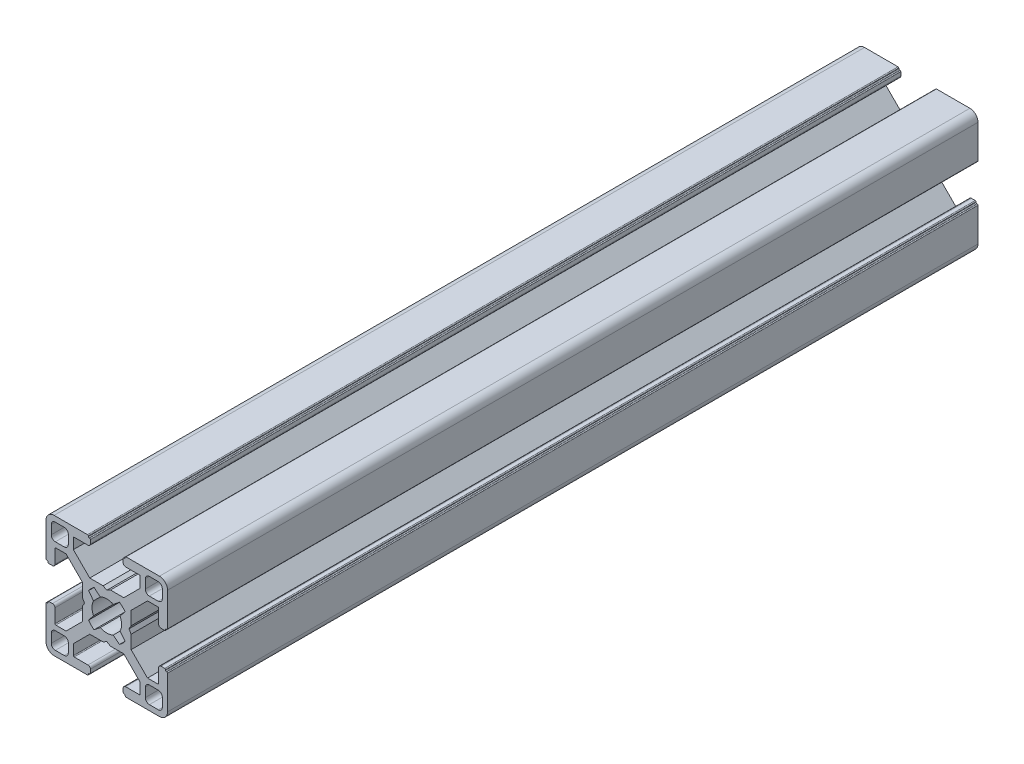
SolidWorks part; units mm, degrees
ref_plane "Front" through (0, 0, 0) normal (0, 0, 1) x (1, 0, 0)
ref_plane "Top" through (0, 0, 0) normal (0, 1, 0) x (1, 0, 0)
ref_plane "Right" through (0, 0, 0) normal (1, 0, 0) x (0, 0, -1)
sketch "Sketch1" plane through (0, 0, 0) normal (0, 0, 1) x (1, 0, 0)
  line L0 (13.7, 12.7) -> (13.7, 10.5)
  line L1 (10.5, 9.5) -> (12.7, 9.5)
  line L2 (9.5, 12.7) -> (9.5, 10.5)
  line L3 (10.5, 13.7) -> (12.7, 13.7)
  line L4 (3.1359, 4.5184) -> (1.6001, 3.2806)
  line L5 (3.2806, 1.6001) -> (4.5053, 3.1547)
  line L6 (6.0045, 0.9) -> (5.4849, 0)
  line L7 (6.0045, 4.2045) -> (6.0045, 0.9)
  line L8 (0, -5.4849) -> (0.9, -6)
  line L9 (0.9, -6) -> (4.2045, -6)
  line L10 (4.2045, -6) -> (8.25, -10.05)
  line L11 (8.25, -10.05) -> (8.25, -12.6)
  line L12 (4.65, -12.8) -> (8.05, -12.8)
  line L13 (4.05, -14.3) -> (4.05, -13.4)
  line L14 (4.25, -14.5) -> (4.35, -14.5)
  line L15 (4.55, -14.8) -> (4.55, -14.7)
  line L16 (4.75, -15) -> (13, -15)
  line L17 (15, -13) -> (15, -4.75)
  line L18 (14.7, -4.55) -> (14.8, -4.55)
  line L19 (14.5, -4.35) -> (14.5, -4.25)
  line L20 (13.4, -4.05) -> (14.3, -4.05)
  line L21 (12.8, -8.05) -> (12.8, -4.65)
  line L22 (12.6, -8.25) -> (10.05, -8.25)
  line L23 (10.05, -8.25) -> (6.0045, -4.2045)
  line L24 (6.0045, -4.2045) -> (6.0045, -0.9)
  line L25 (6.0045, -0.9) -> (5.4849, 0)
  line L26 (10.05, 8.25) -> (6.0045, 4.2045)
  line L27 (12.6, 8.25) -> (10.05, 8.25)
  line L28 (12.8, 8.05) -> (12.8, 4.65)
  line L29 (13.4, 4.05) -> (14.3, 4.05)
  line L30 (14.5, 4.35) -> (14.5, 4.25)
  line L31 (14.7, 4.55) -> (14.8, 4.55)
  line L32 (15, 13) -> (15, 4.75)
  line L33 (4.75, 15) -> (13, 15)
  line L34 (4.55, 14.8) -> (4.55, 14.7)
  line L35 (4.25, 14.5) -> (4.35, 14.5)
  line L36 (4.05, 14.3) -> (4.05, 13.4)
  line L37 (4.65, 12.8) -> (8.05, 12.8)
  line L38 (8.25, 10.05) -> (8.25, 12.6)
  line L39 (4.2045, 6) -> (8.25, 10.05)
  line L40 (0.9, 6) -> (4.2045, 6)
  line L41 (0, 5.4849) -> (0.9, 6)
  line L42 (-13.7, -12.7) -> (-13.7, -10.5)
  line L43 (-10.5, -9.5) -> (-12.7, -9.5)
  line L44 (-9.5, -12.7) -> (-9.5, -10.5)
  line L45 (-10.5, -13.7) -> (-12.7, -13.7)
  line L46 (-3.1359, -4.5184) -> (-1.6001, -3.2806)
  line L47 (-3.2806, -1.6001) -> (-4.5053, -3.1547)
  line L48 (0, 5.4849) -> (-0.9, 6)
  line L49 (-0.9, 6) -> (-4.2045, 6)
  line L50 (-4.2045, 6) -> (-8.25, 10.05)
  line L51 (-8.25, 10.05) -> (-8.25, 12.6)
  line L52 (-4.65, 12.8) -> (-8.05, 12.8)
  line L53 (-4.05, 14.3) -> (-4.05, 13.4)
  line L54 (-4.25, 14.5) -> (-4.35, 14.5)
  line L55 (-4.55, 14.8) -> (-4.55, 14.7)
  line L56 (-4.75, 15) -> (-13, 15)
  line L57 (-15, 13) -> (-15, 4.75)
  line L58 (-14.7, 4.55) -> (-14.8, 4.55)
  line L59 (-14.5, 4.35) -> (-14.5, 4.25)
  line L60 (-13.4, 4.05) -> (-14.3, 4.05)
  line L61 (-12.8, 8.05) -> (-12.8, 4.65)
  line L62 (-12.6, 8.25) -> (-10.05, 8.25)
  line L63 (-10.05, 8.25) -> (-6.0045, 4.2045)
  line L64 (-6.0045, -0.9) -> (-5.4849, 0)
  line L65 (-6.0045, -4.2045) -> (-6.0045, -0.9)
  line L66 (-10.05, -8.25) -> (-6.0045, -4.2045)
  line L67 (-12.6, -8.25) -> (-10.05, -8.25)
  line L68 (-12.8, -8.05) -> (-12.8, -4.65)
  line L69 (-13.4, -4.05) -> (-14.3, -4.05)
  line L70 (-14.5, -4.35) -> (-14.5, -4.25)
  line L71 (-14.7, -4.55) -> (-14.8, -4.55)
  line L72 (-15, -13) -> (-15, -4.75)
  line L73 (-4.75, -15) -> (-13, -15)
  line L74 (-4.55, -14.8) -> (-4.55, -14.7)
  line L75 (-4.25, -14.5) -> (-4.35, -14.5)
  line L76 (-4.05, -14.3) -> (-4.05, -13.4)
  line L77 (3.2806, -1.6001) -> (4.5053, -3.1547)
  line L78 (3.1359, -4.5184) -> (1.6001, -3.2806)
  line L79 (-4.65, -12.8) -> (-8.05, -12.8)
  line L80 (-8.25, -10.05) -> (-8.25, -12.6)
  line L81 (-4.2045, -6) -> (-8.25, -10.05)
  line L82 (-0.9, -6) -> (-4.2045, -6)
  line L83 (0, -5.4849) -> (-0.9, -6)
  line L84 (10.5, -13.7) -> (12.7, -13.7)
  line L85 (9.5, -12.7) -> (9.5, -10.5)
  line L86 (10.5, -9.5) -> (12.7, -9.5)
  line L87 (13.7, -12.7) -> (13.7, -10.5)
  line L88 (-6.0045, 4.2045) -> (-6.0045, 0.9)
  line L89 (-6.0045, 0.9) -> (-5.4849, 0)
  line L90 (-3.2806, 1.6001) -> (-4.5053, 3.1547)
  line L91 (-3.1359, 4.5184) -> (-1.6001, 3.2806)
  line L92 (-10.5, 13.7) -> (-12.7, 13.7)
  line L93 (-9.5, 12.7) -> (-9.5, 10.5)
  line L94 (-10.5, 9.5) -> (-12.7, 9.5)
  line L95 (-13.7, 12.7) -> (-13.7, 10.5)
  line L96 (-23.4857, 0) -> (20.9308, 0) construction
  line L97 (0, 17.9563) -> (0, -17.361) construction
  arc A0 (13.7, 12.7) -> (12.7, 13.7) centre (12.7, 12.7) ccw
  arc A1 (12.7, 9.5) -> (13.7, 10.5) centre (12.7, 10.5) ccw
  arc A2 (9.5, 10.5) -> (10.5, 9.5) centre (10.5, 10.5) ccw
  arc A3 (10.5, 13.7) -> (9.5, 12.7) centre (10.5, 12.7) ccw
  arc A4 (1.6001, 3.2806) -> (-1.6001, 3.2806) centre (0, 0) ccw
  arc A5 (8.25, -12.6) -> (8.05, -12.8) centre (8.05, -12.6) cw
  arc A6 (4.65, -12.8) -> (4.05, -13.4) centre (4.65, -13.4) ccw
  arc A7 (4.05, -14.3) -> (4.25, -14.5) centre (4.25, -14.3) ccw
  arc A8 (4.35, -14.5) -> (4.55, -14.7) centre (4.35, -14.7) cw
  arc A9 (4.55, -14.8) -> (4.75, -15) centre (4.75, -14.8) ccw
  arc A10 (13, -15) -> (15, -13) centre (13, -13) ccw
  arc A11 (15, -4.75) -> (14.8, -4.55) centre (14.8, -4.75) ccw
  arc A12 (14.7, -4.55) -> (14.5, -4.35) centre (14.7, -4.35) cw
  arc A13 (14.5, -4.25) -> (14.3, -4.05) centre (14.3, -4.25) ccw
  arc A14 (13.4, -4.05) -> (12.8, -4.65) centre (13.4, -4.65) ccw
  arc A15 (12.8, -8.05) -> (12.6, -8.25) centre (12.6, -8.05) cw
  arc A16 (4.5053, 3.1547) -> (3.1359, 4.5184) centre (0, 0) ccw
  arc A17 (12.8, 8.05) -> (12.6, 8.25) centre (12.6, 8.05) ccw
  arc A18 (13.4, 4.05) -> (12.8, 4.65) centre (13.4, 4.65) cw
  arc A19 (14.5, 4.25) -> (14.3, 4.05) centre (14.3, 4.25) cw
  arc A20 (14.7, 4.55) -> (14.5, 4.35) centre (14.7, 4.35) ccw
  arc A21 (15, 4.75) -> (14.8, 4.55) centre (14.8, 4.75) cw
  arc A22 (13, 15) -> (15, 13) centre (13, 13) cw
  arc A23 (4.55, 14.8) -> (4.75, 15) centre (4.75, 14.8) cw
  arc A24 (4.35, 14.5) -> (4.55, 14.7) centre (4.35, 14.7) ccw
  arc A25 (4.05, 14.3) -> (4.25, 14.5) centre (4.25, 14.3) cw
  arc A26 (4.65, 12.8) -> (4.05, 13.4) centre (4.65, 13.4) cw
  arc A27 (8.25, 12.6) -> (8.05, 12.8) centre (8.05, 12.6) ccw
  arc A28 (-13.7, -12.7) -> (-12.7, -13.7) centre (-12.7, -12.7) ccw
  arc A29 (-12.7, -9.5) -> (-13.7, -10.5) centre (-12.7, -10.5) ccw
  arc A30 (-9.5, -10.5) -> (-10.5, -9.5) centre (-10.5, -10.5) ccw
  arc A31 (-10.5, -13.7) -> (-9.5, -12.7) centre (-10.5, -12.7) ccw
  arc A32 (-4.5053, -3.1547) -> (-3.1359, -4.5184) centre (0, 0) ccw
  arc A33 (-3.2806, 1.6001) -> (-3.2806, -1.6001) centre (0, 0) ccw
  arc A34 (-8.25, 12.6) -> (-8.05, 12.8) centre (-8.05, 12.6) cw
  arc A35 (-4.65, 12.8) -> (-4.05, 13.4) centre (-4.65, 13.4) ccw
  arc A36 (-4.05, 14.3) -> (-4.25, 14.5) centre (-4.25, 14.3) ccw
  arc A37 (-4.35, 14.5) -> (-4.55, 14.7) centre (-4.35, 14.7) cw
  arc A38 (-4.55, 14.8) -> (-4.75, 15) centre (-4.75, 14.8) ccw
  arc A39 (-13, 15) -> (-15, 13) centre (-13, 13) ccw
  arc A40 (-15, 4.75) -> (-14.8, 4.55) centre (-14.8, 4.75) ccw
  arc A41 (-14.7, 4.55) -> (-14.5, 4.35) centre (-14.7, 4.35) cw
  arc A42 (-14.5, 4.25) -> (-14.3, 4.05) centre (-14.3, 4.25) ccw
  arc A43 (-13.4, 4.05) -> (-12.8, 4.65) centre (-13.4, 4.65) ccw
  arc A44 (-12.8, 8.05) -> (-12.6, 8.25) centre (-12.6, 8.05) cw
  arc A45 (-4.5053, 3.1547) -> (-3.1359, 4.5184) centre (0, 0) cw
  arc A46 (-12.8, -8.05) -> (-12.6, -8.25) centre (-12.6, -8.05) ccw
  arc A47 (-13.4, -4.05) -> (-12.8, -4.65) centre (-13.4, -4.65) cw
  arc A48 (-14.5, -4.25) -> (-14.3, -4.05) centre (-14.3, -4.25) cw
  arc A49 (3.2806, 1.6001) -> (3.2806, -1.6001) centre (0, 0) cw
  arc A50 (4.5053, -3.1547) -> (3.1359, -4.5184) centre (0, 0) cw
  arc A51 (1.6001, -3.2806) -> (-1.6001, -3.2806) centre (0, 0) cw
  arc A52 (-14.7, -4.55) -> (-14.5, -4.35) centre (-14.7, -4.35) ccw
  arc A53 (-15, -4.75) -> (-14.8, -4.55) centre (-14.8, -4.75) cw
  arc A54 (-13, -15) -> (-15, -13) centre (-13, -13) cw
  arc A55 (-4.55, -14.8) -> (-4.75, -15) centre (-4.75, -14.8) cw
  arc A56 (10.5, -13.7) -> (9.5, -12.7) centre (10.5, -12.7) cw
  arc A57 (9.5, -10.5) -> (10.5, -9.5) centre (10.5, -10.5) cw
  arc A58 (12.7, -9.5) -> (13.7, -10.5) centre (12.7, -10.5) cw
  arc A59 (13.7, -12.7) -> (12.7, -13.7) centre (12.7, -12.7) cw
  arc A60 (-4.35, -14.5) -> (-4.55, -14.7) centre (-4.35, -14.7) ccw
  arc A61 (-4.05, -14.3) -> (-4.25, -14.5) centre (-4.25, -14.3) cw
  arc A62 (-4.65, -12.8) -> (-4.05, -13.4) centre (-4.65, -13.4) cw
  arc A63 (-8.25, -12.6) -> (-8.05, -12.8) centre (-8.05, -12.6) ccw
  arc A64 (-10.5, 13.7) -> (-9.5, 12.7) centre (-10.5, 12.7) cw
  arc A65 (-9.5, 10.5) -> (-10.5, 9.5) centre (-10.5, 10.5) cw
  arc A66 (-12.7, 9.5) -> (-13.7, 10.5) centre (-12.7, 10.5) cw
  arc A67 (-13.7, 12.7) -> (-12.7, 13.7) centre (-12.7, 12.7) cw
  point P81 (15, 15)
  point P82 (0, 15)
  point P203 (0, -15)
  point P204 (15, -15)
  point P206 (0, 0)
  point P207 (15, 0)
  point P219 (-15, 0)
  point P220 (-15, -15)
  point P221 (-15, 15)
  dimension "D6" = 7.3
  dimension "D7" = 11
  dimension "D1" = 30
  dimension "D2" = 15
  dimension "D3" = 30
  dimension "D4" = 8.1
  dimension "D5" = 9
  dimension "D8" = 8.1
extrude "Base-Extrude" add sketch "Sketch1" against normal blind 200
